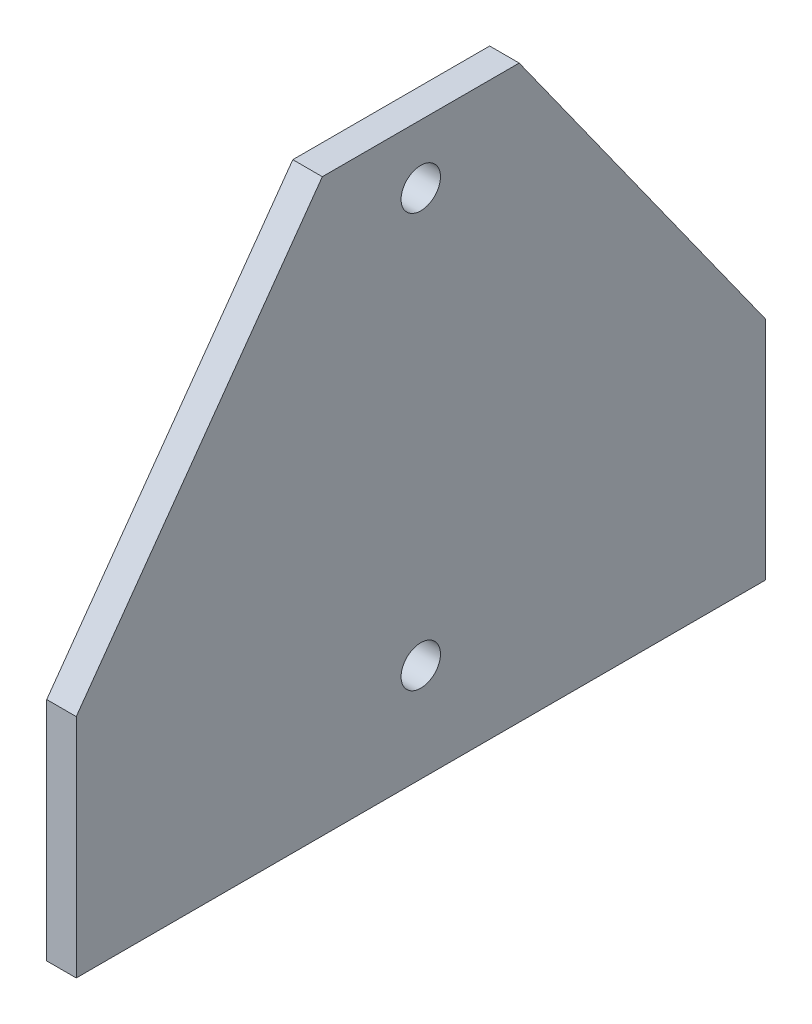
SolidWorks part; units mm, degrees
ref_plane "Ön Düzlem" through (0, 0, 0) normal (0, 0, 1) x (1, 0, 0)
ref_plane "Üst Düzlem" through (0, 0, 0) normal (0, 1, 0) x (1, 0, 0)
ref_plane "Sağ Düzlem" through (0, 0, 0) normal (1, 0, 0) x (0, 0, -1)
sketch "Sketch1" plane through (0, 0, 0) normal (1, 0, 0) x (0, 0, -1)
  line L0 (0, 0) -> (25, 35)
  line L2 (0, 0) -> (0, -23)
  line L3 (0, -23) -> (70, -23)
  line L4 (70, 0) -> (70, -23)
  line L5 (25, 35) -> (45, 35)
  line L6 (45, 35) -> (70, 0)
  line L7 (35, -23) -> (35, 59.5166) construction
  circle A0 centre (35, -13) radius 2
  circle A1 centre (35, 29) radius 2
  dimension "D6" = 4
  dimension "D7" = 4
  dimension "D1" = 23
  dimension "D2" = 70
  dimension "D3" = 20
  dimension "D4" = 35
  dimension "D5" = 10
  dimension "D8" = 6
extrude "Boss-Extrude1" add sketch "Sketch1" along normal blind 3
